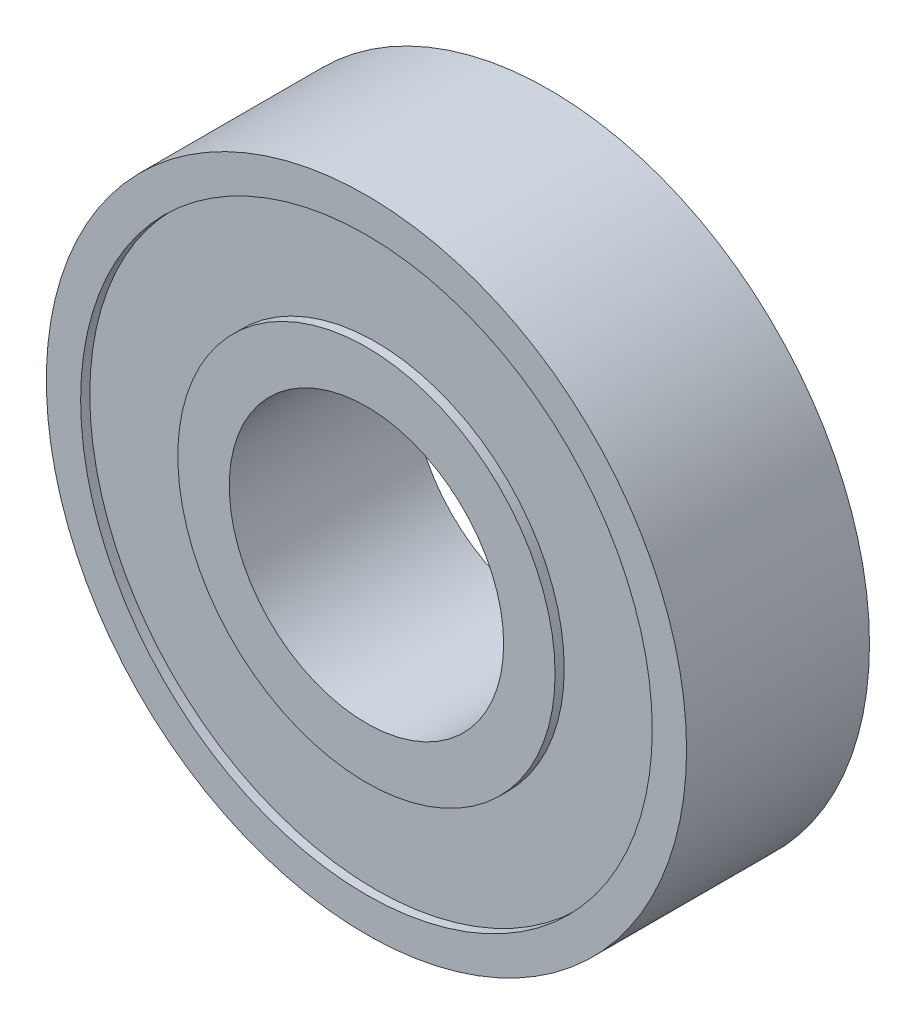
SolidWorks part; units mm, degrees
material "Chrome Stainless Steel"
ref_plane "Front" through (0, 0, 0) normal (0, 0, 1) x (1, 0, 0)
ref_plane "Top" through (0, 0, 0) normal (0, 1, 0) x (1, 0, 0)
ref_plane "Right" through (0, 0, 0) normal (1, 0, 0) x (0, 0, -1)
sketch "Sketch1" plane through (0, 0, 0) normal (0, 0, 1) x (1, 0, 0)
  circle A0 centre (0, 0) radius 14
  circle A1 centre (0, 0) radius 6
  dimension "D1" = 28
  dimension "D2" = 12
extrude "Extrude1" add sketch "Sketch1" along normal mid plane 8
sketch "Sketch2" plane through (0, 0, 4) normal (0, 0, 1) x (1, 0, 0)
  circle A2 centre (0, 0) radius 8.25
  circle A3 centre (0, 0) radius 8.25
  circle A5 centre (0, 0) radius 12.5
  circle A6 centre (0, 0) radius 12.5
  dimension "D1" = 2.25
  dimension "D2" = 1.5
extrude "Cut-Extrude1" cut sketch "Sketch2" against normal blind 0.4
mirror "Mirror1" about plane through (0, 0, 0) normal (0, 0, 1) of "Cut-Extrude1"
